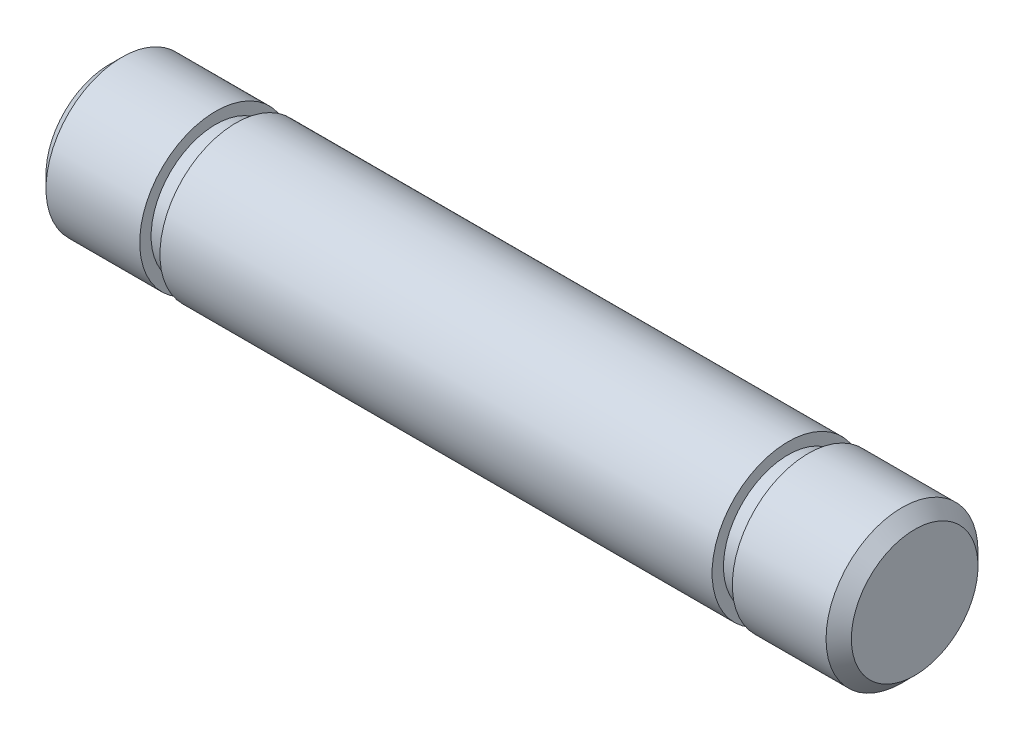
SolidWorks part; units mm, degrees
ref_plane "Alzado" through (0, 0, 0) normal (1, 0, 0) x (0, 1, 0)
ref_plane "Planta" through (0, 0, 0) normal (0, 0, 1) x (0, 1, 0)
ref_plane "Vista lateral" through (0, 0, 0) normal (0, 1, 0) x (-1, 0, 0)
sketch "Croquis1" plane through (0, 0, 0) normal (0, 1, 0) x (-1, 0, 0)
  line L1 (-10.9, 3) -> (10.9, 3)
  line L6 (15.9, 3) -> (15.9, 0)
  line L7 (-15.9, 0) -> (15.9, 0) construction
  line L22 (-15.9, 0) -> (15.9, 0)
  line L23 (10.9, 3) -> (10.9, 2.55)
  line L24 (10.9, 2.55) -> (11.7, 2.55)
  line L25 (11.7, 2.55) -> (11.7, 3)
  line L26 (11.7, 3) -> (15.9, 3)
  line L27 (0, 0) -> (0, 3) construction
  line L28 (-11.7, 3) -> (-15.9, 3)
  line L29 (-11.7, 2.55) -> (-11.7, 3)
  line L30 (-10.9, 2.55) -> (-11.7, 2.55)
  line L31 (-10.9, 3) -> (-10.9, 2.55)
  line L32 (-15.9, 3) -> (-15.9, 0)
  dimension "D1" = 5
  dimension "D2" = 6
  dimension "D3" = 21.8
  dimension "D5" = 0.8
  dimension "D7" = 0.45
revolve "Revolución1" add sketch "Croquis1" angle 360 about L7
chamfer "Chaflán1" distance 0.5 angle 45 2 edges at (15.9, 0, -3) (-15.9, 0, -3)
equation "\"ancho_circlip\"=0.8"
equation "\"ranura_circlip\"=0.45"
